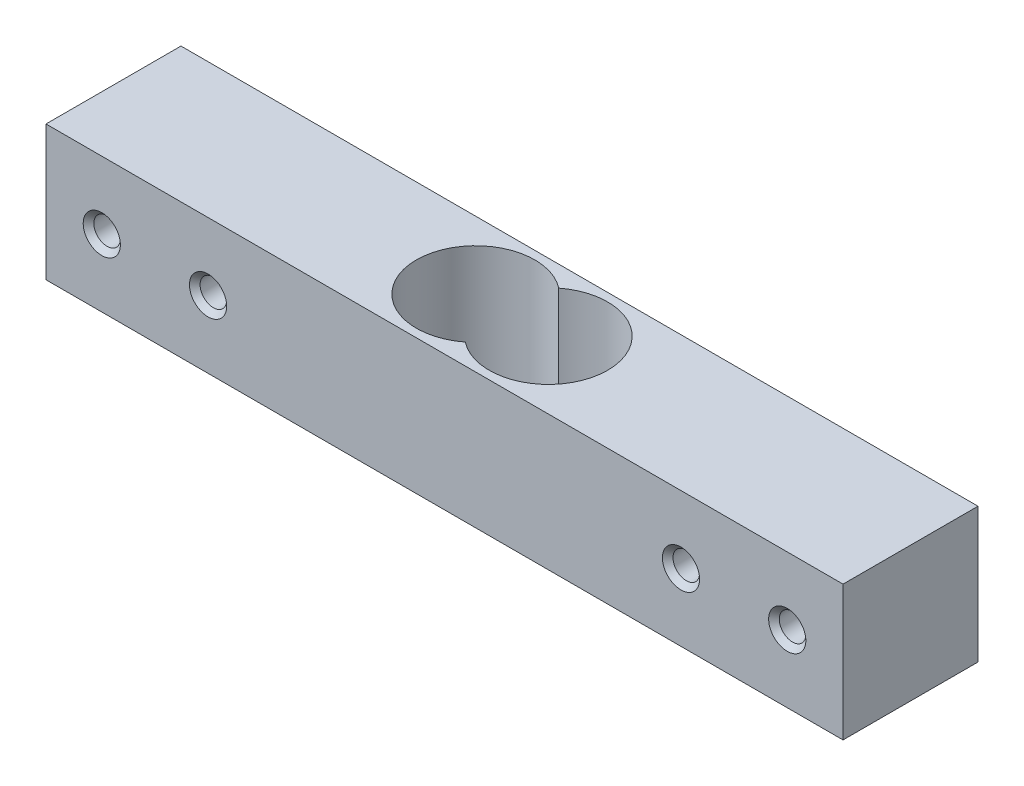
SolidWorks part; units mm, degrees
ref_plane "Front Plane" through (0, 0, 0) normal (0, 0, 1) x (1, 0, 0)
ref_plane "Top Plane" through (0, 0, 0) normal (0, 1, 0) x (1, 0, 0)
ref_plane "Right Plane" through (0, 0, 0) normal (1, 0, 0) x (0, 0, -1)
sketch "Sketch1" plane through (0, 0, 0) normal (0, 1, 0) x (1, 0, 0)
  line L0 (0, 0) -> (0, 50927.2988) construction
  line L1 (-37.5, -6.35) -> (37.5, -6.35)
  line L2 (-37.5, -6.35) -> (-37.5, 6.35)
  line L3 (-37.5, 6.35) -> (37.5, 6.35)
  line L4 (37.5, -6.35) -> (37.5, 6.35)
  line L5 (-37.5, -6.35) -> (37.5, 6.35) construction
  line L6 (-37.5, 6.35) -> (37.5, -6.35) construction
  circle A0 centre (-3.425, 0) radius 5.575
  circle A1 centre (3.425, 0) radius 5.575
  point P0 (0, 0)
  dimension "D1" = 11.15
  dimension "D2" = 12.7
  dimension "D3" = 75
  dimension "D4" = 6.85
extrude "Boss-Extrude1" add sketch "Sketch1" along normal mid plane 12.7 contours L1 L4 L3 L2 A1 A0
sketch "Sketch2" plane through (0, 0, -6.35) normal (0, 0, -1) x (-1, 0, 0)
  line L0 (-32.25, 0) -> (-22.25, 0) construction
  line L1 (-22.25, 0) -> (22.25, 0) construction
  line L2 (22.25, 0) -> (32.25, 0) construction
  point P6 (0, 0)
  dimension "D1" = 64.5
  dimension "D2" = 44.5
hole_wizard "M3 Tapped Hole1" positions "Sketch3" profile "Sketch5" tap size "M3" standard "DIN" end condition through all
sketch "Sketch3" plane through (0, 0, -6.35) normal (0, 0, -1) x (-1, 0, 0)
  point P0 (32.25, 0)
  point P3 (22.25, 0)
  point P6 (-22.25, 0)
  point P9 (-32.25, 0)
cosmetic thread "Hole Thread1" parameters "D2"=3
cosmetic thread "Hole Thread2" parameters "D2"=3
cosmetic thread "Hole Thread3" parameters "D2"=3
cosmetic thread "Hole Thread4" parameters "D2"=3
sketch "Sketch5" plane through (-32.25, 0, -6.35) normal (1, 0, 0) x (0, 1, 0)
  line L0 (0, 0) -> (0, 12.7)
  line L1 (0, 12.7) -> (1.75, 12.7)
  line L2 (1.25, 12.2) -> (1.25, 0.5)
  line L3 (1.25, 0.5) -> (1.75, 0)
  line L5 (1.75, 0) -> (0, 0)
  line L6 (-1.25, 0.5) -> (-1.75, 0) construction
  line L7 (1.75, 12.7) -> (1.25, 12.2)
  line L8 (-1.75, 12.7) -> (-1.25, 12.2) construction
  line L11 (0, -6.35) -> (0, 107.95) construction
  dimension "Thru Tap Drill Dia." = 2.5
  dimension "Thru Tap Drill Depth" = 12.7
  dimension "Near C'Sink Dia." = 3.5
  dimension "Near C'Sink Angle" = 90
  dimension "Far C'Sink Dia." = 3.5
  dimension "Far C'Sink Angle" = 90
